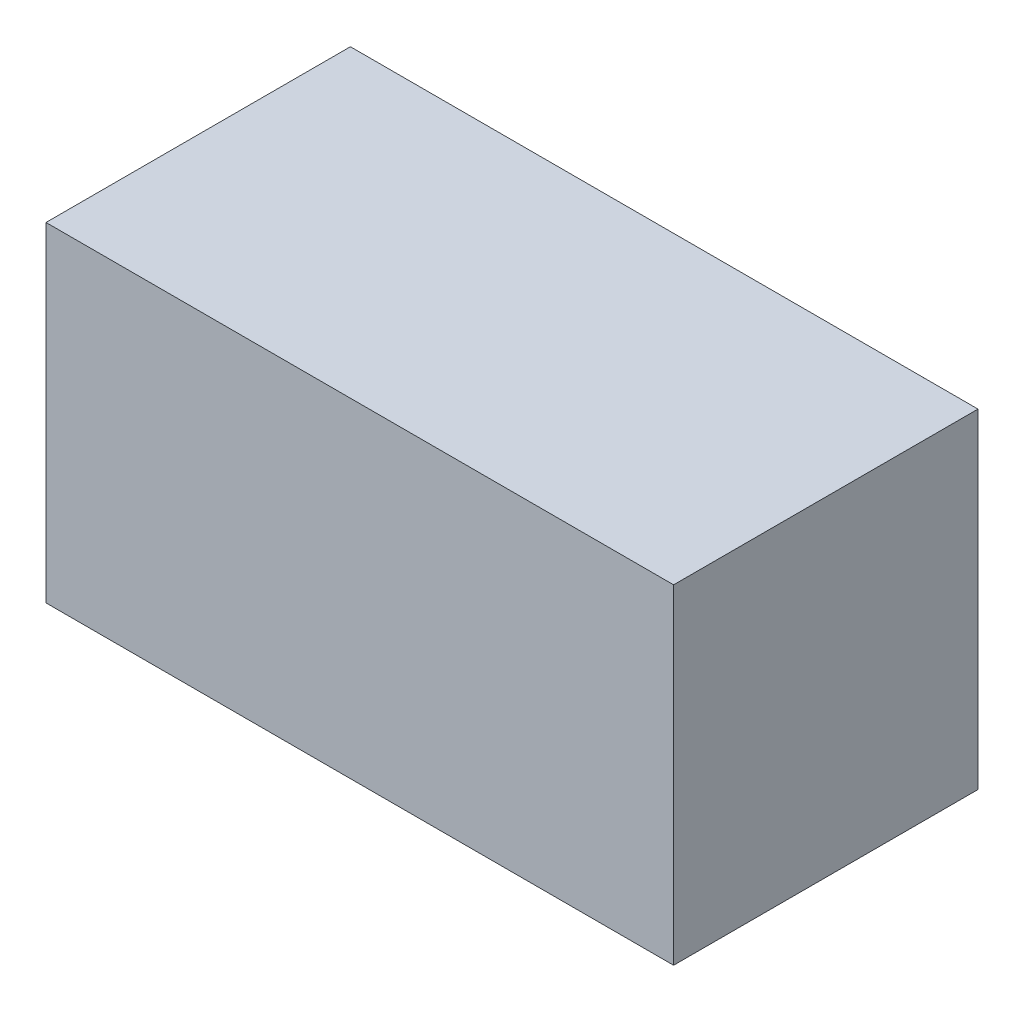
SolidWorks part; units mm, degrees
ref_plane "Front Plane" through (0, 0, 0) normal (0, 0, 1) x (1, 0, 0)
ref_plane "Top Plane" through (0, 0, 0) normal (0, 1, 0) x (1, 0, 0)
ref_plane "Right Plane" through (0, 0, 0) normal (1, 0, 0) x (0, 0, -1)
sketch "Sketch1" plane through (0, 0, 0) normal (0, 1, 0) x (1, 0, 0)
  line L1 (0, 0) -> (20, 0)
  line L2 (0, 0) -> (0, 9.7)
  line L3 (0, 9.7) -> (20, 9.7)
  line L4 (20, 0) -> (20, 9.7)
  dimension "D1" = 9.7
  dimension "D2" = 20
extrude "Boss-Extrude1" add sketch "Sketch1" along normal blind 10.5
